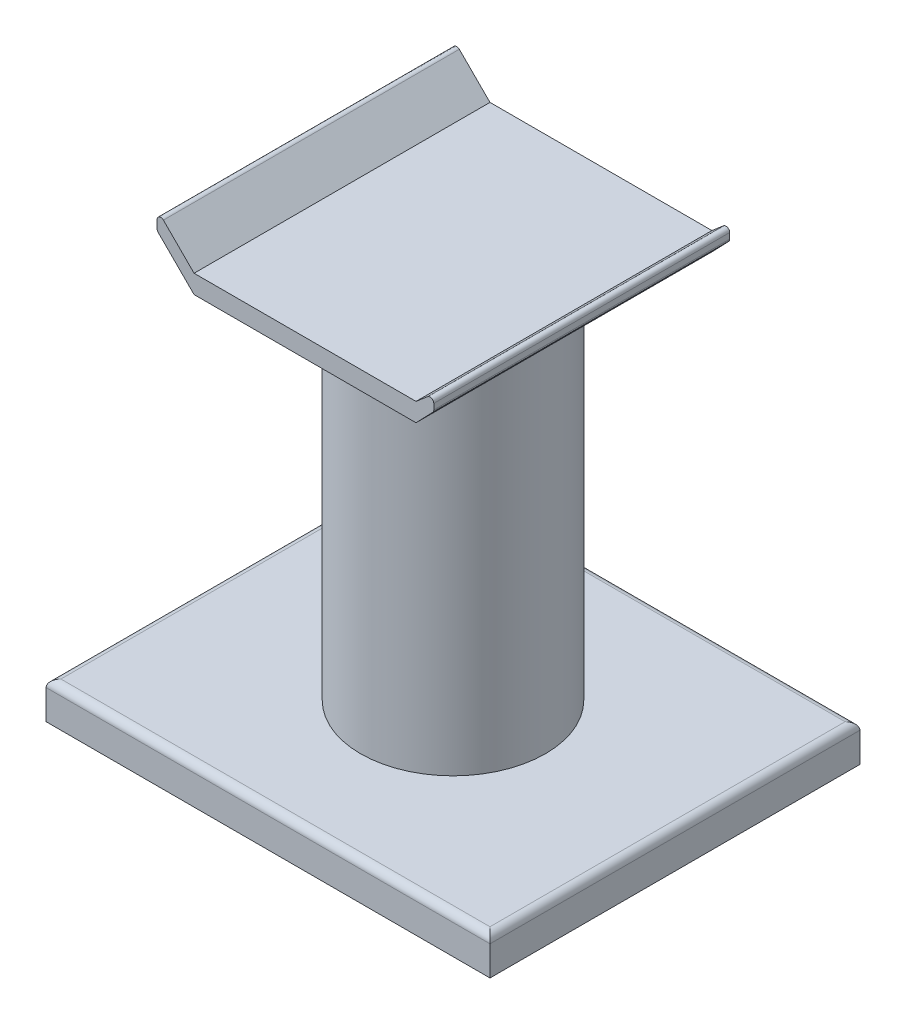
SolidWorks part; units mm, degrees
ref_plane "前视基准面" through (0, 0, 0) normal (0, 0, 1) x (1, 0, 0)
ref_plane "上视基准面" through (0, 0, 0) normal (0, 1, 0) x (1, 0, 0)
ref_plane "右视基准面" through (0, 0, 0) normal (1, 0, 0) x (0, 0, -1)
other "Configuration Table"
sketch "草图1" plane through (0, 0, 0) normal (0, 1, 0) x (1, 0, 0)
  line L1 (-60, 50) -> (60, 50)
  line L2 (-60, 50) -> (-60, -50)
  line L3 (-60, -50) -> (60, -50)
  line L4 (60, 50) -> (60, -50)
  line L5 (-60, 50) -> (60, -50) construction
  line L6 (-60, -50) -> (60, 50) construction
  point P0 (0, 0)
extrude "凸台-拉伸1" add sketch "草图1" along normal blind 10
sketch "草图2" plane through (0, 10, 0) normal (0, 1, 0) x (1, 0, 0)
  circle A0 centre (0, 0) radius 25
extrude "凸台-拉伸2" add sketch "草图2" along normal blind 100
sketch "草图3" plane through (0, 110, 0) normal (0, 1, 0) x (1, 0, 0)
  line L1 (-30, 40) -> (30, 40)
  line L2 (-30, 40) -> (-30, -40)
  line L3 (-30, -40) -> (30, -40)
  line L4 (30, 40) -> (30, -40)
  line L5 (-30, 40) -> (30, -40) construction
  line L6 (-30, -40) -> (30, 40) construction
  point P0 (0, 0)
extrude "凸台-拉伸3" add sketch "草图3" along normal blind 5
ref_plane "基准面5" through (-30, 115, 40) normal (1, 0, 0) x (0, 0, -1)
sketch "草图5" plane through (0, 0, 40) normal (0, 0, 1) x (1, 0, 0)
  line L0 (-30, 115) -> (-30, 125) construction
  line L1 (-30, 98.5) -> (-30, 131.5) construction
  line L2 (-30, 115) -> (30, 115) construction
  line L3 (-30, 125) -> (-40, 125) construction
  line L4 (-40, 125) -> (-30, 115)
  line L5 (-40, 125) -> (-40, 120)
  line L6 (-40, 120) -> (-30, 110)
  line L7 (-30, 110) -> (30, 110) construction
  line L8 (-30, 115) -> (-30, 110)
extrude "凸台-拉伸4" add sketch "草图5" against normal blind 80
sketch "草图6" plane through (0, 0, 40) normal (0, 0, 1) x (1, 0, 0)
  line L0 (30, 115) -> (34.8052, 119.1105)
  line L1 (34.8052, 119.1105) -> (34.8052, 115)
  line L2 (34.8052, 115) -> (30, 110)
  line L3 (30, 110) -> (30, 115)
extrude "凸台-拉伸5" add sketch "草图6" against normal blind 80
fillet "圆角2" radius 1 1 edges at (-40, 125, 0)
fillet "圆角3" radius 1 1 edges at (34.8052, 119.1105, 0)
fillet "圆角4" radius 1 1 edges at (-40, 120, 0)
fillet "圆角5" radius 1 1 edges at (34.8052, 115, 0)
fillet "圆角6" radius 2 4 edges at (-60, 10, 0) (0, 10, 50) (60, 10, 0) (0, 10, -50)
